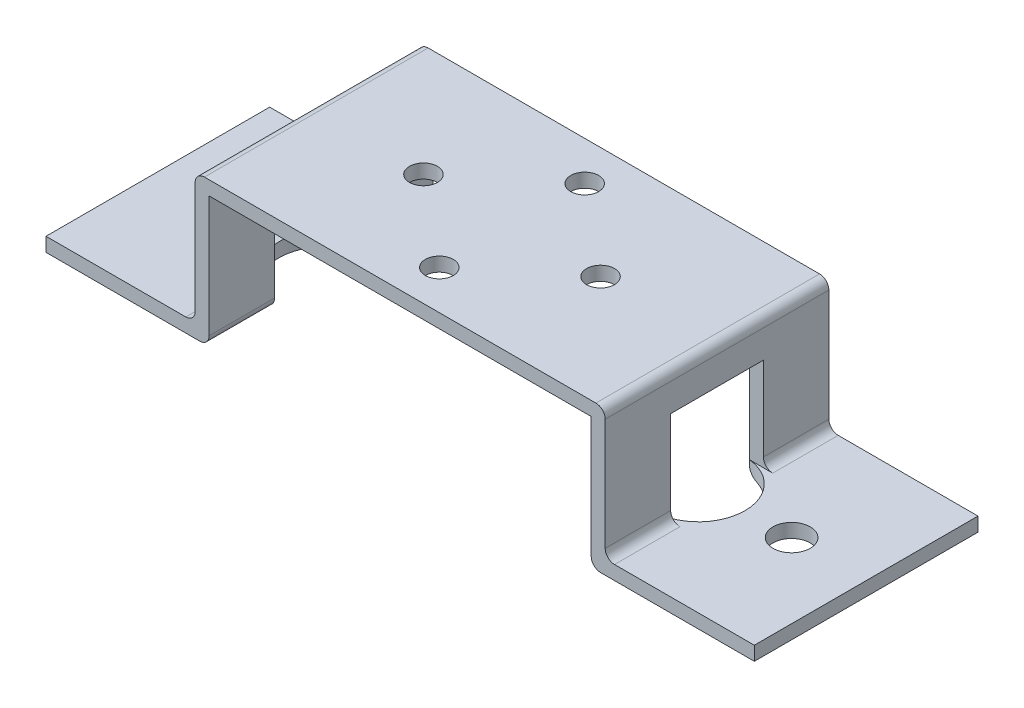
SolidWorks part; units mm, degrees
ref_plane "Front Plane" through (0, 0, 0) normal (0, 0, 1) x (1, 0, 0)
ref_plane "Top Plane" through (0, 0, 0) normal (0, 1, 0) x (1, 0, 0)
ref_plane "Right Plane" through (0, 0, 0) normal (1, 0, 0) x (0, 0, -1)
sketch3d "3DSketch1"
  line L0 (0, 0, 0) -> (17.5, 0, 0)
  line L1 (17.5, 0, 0) -> (17.5, 14, 0)
  line L2 (17.5, 14, 0) -> (58.5, 14, 0)
  line L3 (58.5, 14, 0) -> (58.5, 0, 0)
  line L4 (58.5, 0, 0) -> (76, 0, 0)
  line L5 (76, 0, 0) -> (76, 1.5, 0)
  line L6 (76, 1.5, 0) -> (60, 1.5, 0)
  line L7 (60, 1.5, 0) -> (60, 15.5, 0)
  line L8 (60, 15.5, 0) -> (16, 15.5, 0)
  line L9 (16, 15.5, 0) -> (16, 1.5, 0)
  line L10 (16, 1.5, 0) -> (0, 1.5, 0)
  line L11 (0, 1.5, 0) -> (0, 0, 0)
  line L12 (38, 15.5, 0) -> (38, 14, 0) construction
  line L13 (16, 8.5, 0) -> (17.5, 8.5, 0) construction
  line L14 (8, 1.5, 0) -> (8, 0, 0) construction
  point P19 (0, 0, 0)
  point P20 (38.7601, 14.2068, 0)
  dimension "D3" = 41
  dimension "D5" = 1.5
  dimension "D7" = 14
  dimension "D8" = 44
  dimension "D9" = 16
extrude "Boss-Extrude2" add sketch "3DSketch1" along direction (0, 0, 1) on the side of the normal blind 24 contours L0 L1 L2 L3 L4 L5 L6 L7 L8 L9 L10 L11
sketch "Sketch12" plane through (0, 1.5, 0) normal (0, 1, 0) x (1, 0, 0)
  line L0 (0, -12) -> (76, -12) construction
  line L1 (76, 0) -> (76, -24) construction
  line L2 (0, 0) -> (0, -24) construction
  point P2 (79.5, -20.5)
  point P5 (0, -20.5)
sketch "Sketch17" plane through (0, 1.5, 0) normal (0, 1, 0) x (1, 0, 0)
  line L0 (0, -12) -> (76, -12) construction
  line L1 (68, -12) -> (76, -12) construction
  line L2 (76, 0) -> (76, -24) construction
  line L3 (8, -12) -> (0, -12) construction
  line L4 (0, 0) -> (0, -24) construction
  circle A0 centre (8, -12) radius 2
  circle A1 centre (68, -12) radius 2
  point P9 (0, -15)
  dimension "D3" = 4
  dimension "D1" = 60
extrude "Cut-Extrude1" cut sketch "Sketch17" against normal through all both and the other way through all
sketch "Sketch18" plane through (0, 15.5, 0) normal (0, 1, 0) x (1, 0, 0)
  line L0 (16, -12) -> (60, -12) construction
  line L1 (16, 0) -> (16, -24) construction
  line L2 (60, 0) -> (60, -24) construction
  line L3 (38, -12) -> (38, -24) construction
  line L4 (38, -24) -> (38, 0) construction
  line L5 (60, -24) -> (16, -24) construction
  line L6 (60, 0) -> (16, 0) construction
  point P8 (39, -41)
  point P12 (39, 0)
hole_wizard "Ø3.0mm Dowel Hole1" positions "Sketch20" profile "Sketch21" hole size "Ø3.0" standard "ANSI Metric" end condition through all
sketch "Sketch20" plane through (0, 15.5, 0) normal (0, 1, 0) x (1, 0, 0)
  line L0 (0, -12) -> (76, -12) construction
  line L1 (38, 0) -> (38, -24) construction
  line L2 (16, -12) -> (60, -12) construction
  point P0 (28.5, -12)
  point P11 (47.5, -12)
  point P12 (38, -19.8)
  point P21 (38, -4.2)
  dimension "D1" = 19
  dimension "D2" = 15.6
sketch "Sketch21" plane through (28.5, 15.5, 12) normal (1, 0, 0) x (0, 0, 1)
  line L0 (0, 0) -> (0, 15.5001)
  line L1 (0, 15.5001) -> (1.5, 15.5001)
  line L2 (1.5, 15.5001) -> (1.5, 0)
  line L5 (1.5, 0) -> (0, 0)
  line L11 (0, -6.35) -> (0, 107.95) construction
  dimension "Thru Hole Dia." = 3
  dimension "Thru Hole Depth" = 15.5001
sketch "Sketch22" plane through (0, 1.5, 0) normal (0, 1, 0) x (1, 0, 0)
  line L0 (38, 0) -> (38, -24) construction
  circle A0 centre (18, -12) radius 5
  circle A1 centre (58, -12) radius 5
  dimension "D1" = 10
extrude "Cut-Extrude2" cut sketch "Sketch22" against normal up to surface (1.5 mm away) up to face at (8, 0, 10)
sketch "Sketch23" plane through (16, 0, 0) normal (-1, 0, 0) x (0, 0, 1)
  line L0 (16.9749, 1.5) -> (16.9749, 0) construction
  line L1 (7.0251, 1.5) -> (16.9749, 1.5)
  line L2 (7.0251, 1.5) -> (7.0251, 11.5)
  line L3 (7.0251, 11.5) -> (16.9749, 11.5)
  line L4 (16.9749, 1.5) -> (16.9749, 11.5)
  dimension "D1" = 10
extrude "Cut-Extrude3" cut sketch "Sketch23" against normal through all both and the other way through all
fillet "Fillet1" radius 1 10 edges
